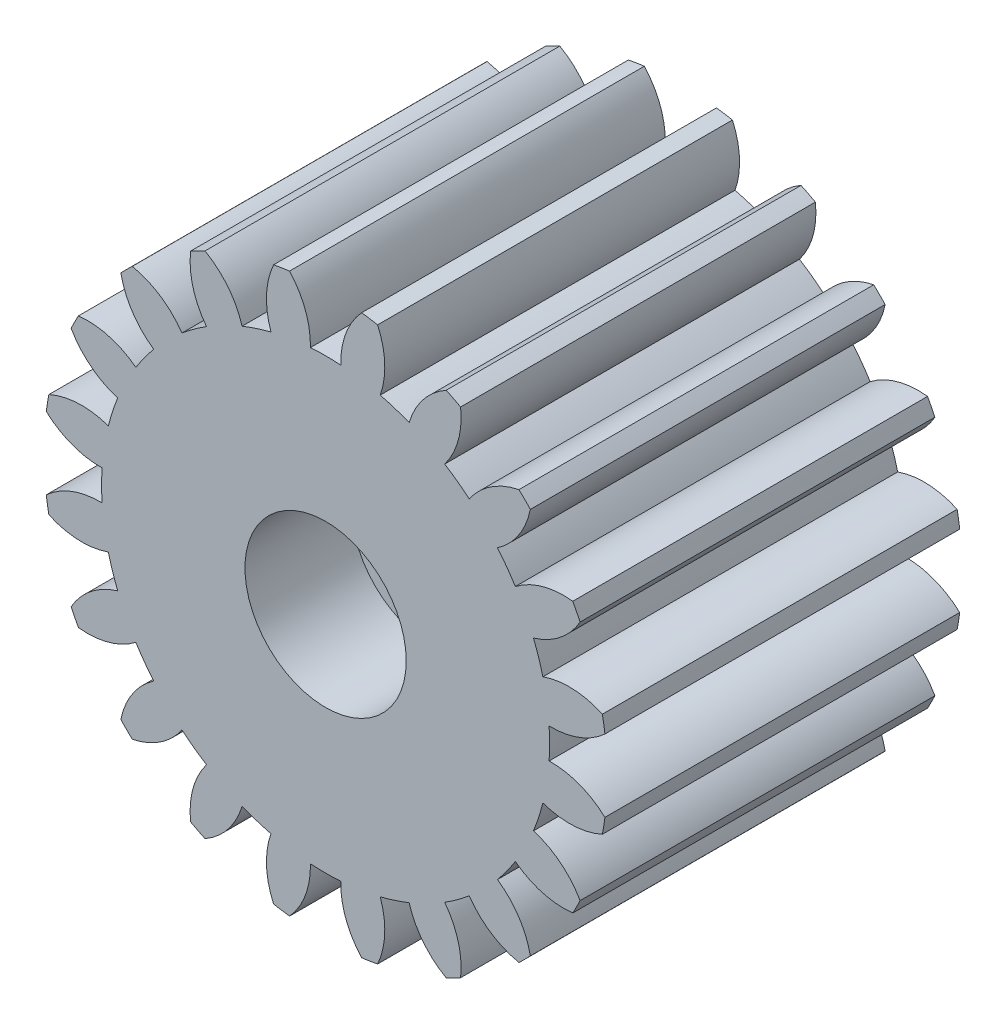
SolidWorks part; units mm, degrees
ref_plane "Front Plane" through (0, 0, 0) normal (0, 0, 1) x (1, 0, 0)
ref_plane "Top Plane" through (0, 0, 0) normal (0, 1, 0) x (1, 0, 0)
ref_plane "Right Plane" through (0, 0, 0) normal (1, 0, 0) x (0, 0, -1)
sketch "Sketch1" plane through (0, 0, 0) normal (0, 0, 1) x (1, 0, 0)
  circle A0 centre (0, 0) radius 8.7312
  dimension "D1" = 17.4625
extrude "Boss-Extrude1" add sketch "Sketch1" along normal blind 11
sketch "Sketch2" plane through (0, 0, 11) normal (0, 0, 1) x (1, 0, 0)
  line L0 (0, 0) -> (50000, 0) construction
  line L2 (6.9293, 0.471) -> (49886.4223, 3391.0136)
  line L3 (9.1709, -1.7793) -> (9.1709, 1.7793)
  circle A0 centre (0, 0) radius 7.9375 construction
  circle A1 centre (0, 0) radius 8.7312 construction
  circle A3 centre (0, 0) radius 8.7312 construction
  arc A4 (6.9293, 0.471) -> (7.1261, 0.4844) centre (6.7796, 4.1281) ccw
  arc A6 (6.9293, -0.471) -> (6.9293, 0.471) centre (0, 0) ccw
  arc A7 (6.9293, 0.471) -> (9.1709, 1.7793) centre (6.9936, 2.9353) ccw
  arc A8 (7.9107, 0.6471) -> (7.9111, 0.6472) centre (6.7796, 4.1281) ccw
  arc A9 (6.9293, -0.471) -> (9.1709, -1.7793) centre (6.9936, -2.9353) cw
  dimension "D1" = 0.7937
  dimension "D2" = 0.6472
  dimension "D4" = 17.4625
  dimension "D6" = 0.471
extrude "Cut-Extrude1" cut sketch "Sketch2" against normal through all contours A6 A9 L3 A7
pattern_circular "CirPattern1" count 20 over 360 about axis through (0, 0, 0) along (0, 0, 1) of "Cut-Extrude1"
sketch "Sketch4" plane through (0, 0, 11) normal (0, 0, 1) x (1, 0, 0)
  circle A0 centre (0, 0) radius 2.5
  dimension "D1" = 5
extrude "Cut-Extrude2" cut sketch "Sketch4" against normal blind 3.3
sketch "Sketch5" plane through (0, 0, 7.7) normal (0, 0, 1) x (1, 0, 0)
  circle A0 centre (0, 0) radius 1
  dimension "D1" = 2
extrude "Cut-Extrude3" cut sketch "Sketch5" against normal through all
